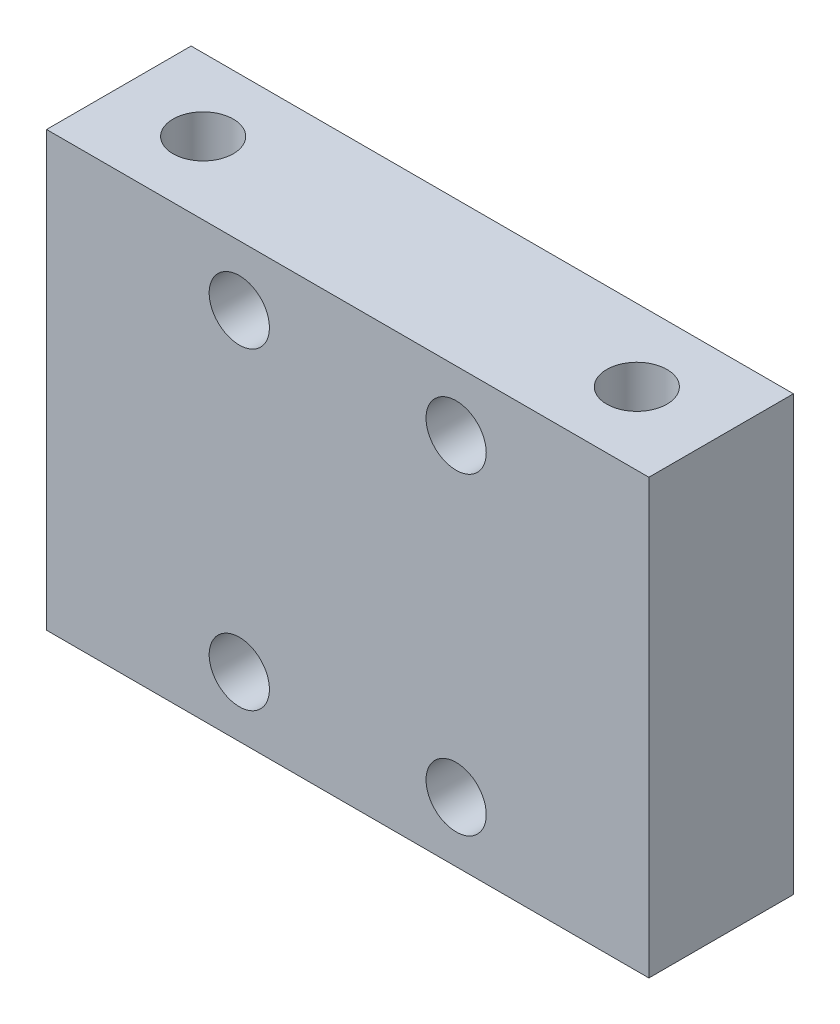
SolidWorks part; units mm, degrees
material "6061 合金"
ref_plane "前视基准面" through (0, 0, 0) normal (0, 0, 1) x (1, 0, 0)
ref_plane "上视基准面" through (0, 0, 0) normal (0, 1, 0) x (1, 0, 0)
ref_plane "右视基准面" through (0, 0, 0) normal (1, 0, 0) x (0, 0, -1)
sketch "草图1" plane through (0, 0, 0) normal (0, 0, 1) x (1, 0, 0)
  line L1 (-12.5, -9) -> (12.5, -9)
  line L2 (-12.5, -9) -> (-12.5, 9)
  line L3 (-12.5, 9) -> (12.5, 9)
  line L4 (12.5, -9) -> (12.5, 9)
  line L5 (-12.5, -9) -> (12.5, 9) construction
  line L6 (-12.5, 9) -> (12.5, -9) construction
  point P0 (0, 0)
  dimension "D1" = 18
  dimension "D2" = 25
extrude "凸台-拉伸1" add sketch "草图1" along normal mid plane 6
sketch "草图2" plane through (0, 9, 0) normal (0, 1, 0) x (1, 0, 0)
  line L0 (-9, 0) -> (9, 0) construction
  point P4 (0, 0)
  dimension "D1" = 18
hole_wizard "M3 螺纹孔1" positions "草图3" profile "草图4" tap size "M3" standard "GB" end condition through all
sketch "草图3" plane through (0, 9, 0) normal (0, 1, 0) x (1, 0, 0)
  point P0 (-9, 0)
  point P3 (9, 0)
cosmetic thread "孔螺蚊线1"
cosmetic thread "孔螺蚊线2"
sketch "草图4" plane through (-9, 9, 0) normal (1, 0, 0) x (0, 0, 1)
  line L0 (0, 0) -> (0, 18)
  line L1 (0, 18) -> (1.25, 18)
  line L2 (1.25, 18) -> (1.25, 0)
  line L5 (1.25, 0) -> (0, 0)
  line L11 (0, -6.35) -> (0, 107.95) construction
  dimension "通孔螺纹孔钻头直径" = 2.5
  dimension "通孔螺纹孔钻头深度" = 18
sketch "草图5" plane through (0, 0, 3) normal (0, 0, 1) x (1, 0, 0)
  line L0 (-9, 9) -> (9, 9) construction
  line L1 (-4.5, -6.5) -> (4.5, -6.5) construction
  line L2 (-4.5, -6.5) -> (-4.5, 6.5) construction
  line L3 (-4.5, 6.5) -> (4.5, 6.5) construction
  line L4 (4.5, -6.5) -> (4.5, 6.5) construction
  line L5 (-4.5, -6.5) -> (4.5, 6.5) construction
  line L6 (-4.5, 6.5) -> (4.5, -6.5) construction
  point P0 (0, 0)
  dimension "D1" = 9
  dimension "D2" = 2.5
hole_wizard "M3 螺纹孔2" positions "草图6" profile "草图7" tap size "M3" standard "GB"
sketch "草图6" plane through (0, 0, 3) normal (0, 0, 1) x (1, 0, 0)
  point P0 (-4.5, -6.5)
  point P3 (4.5, -6.5)
  point P6 (4.5, 6.5)
  point P9 (-4.5, 6.5)
sketch "草图7" plane through (-4.5, -6.5, 3) normal (1, 0, 0) x (0, -1, 0)
  line L0 (0, 0) -> (0, 9.2511)
  line L1 (0, 9.2511) -> (1.25, 8.5)
  line L2 (1.25, 8.5) -> (1.25, 0)
  line L5 (1.25, 0) -> (0, 0)
  line L10 (0, 9.2511) -> (-1.25, 8.5) construction
  line L11 (0, -6.35) -> (0, 107.95) construction
  dimension "螺纹孔钻头直径" = 2.5
  dimension "螺纹孔钻头深度" = 8.5
  dimension "导头角度" = 118
cosmetic thread "孔螺蚊线3"
cosmetic thread "孔螺蚊线4"
cosmetic thread "孔螺蚊线5"
cosmetic thread "孔螺蚊线6"
